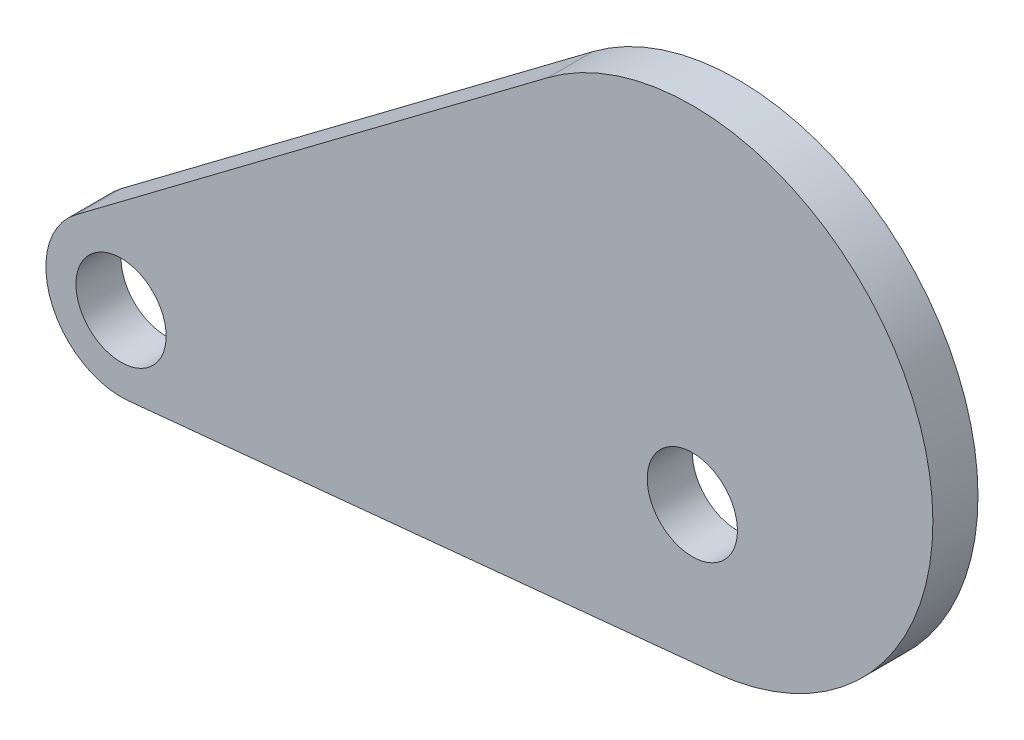
SolidWorks part; units mm, degrees
ref_plane "正面" through (0, 0, 0) normal (0, 0, 1) x (1, 0, 0)
ref_plane "平面" through (0, 0, 0) normal (0, 1, 0) x (1, 0, 0)
ref_plane "右側面" through (0, 0, 0) normal (1, 0, 0) x (0, 0, -1)
sketch "ｽｹｯﾁ1" plane through (0, 0, 0) normal (0, 0, 1) x (1, 0, 0)
  line L0 (9.387, 23.6902) -> (-22.0041, 0.0969)
  line L1 (19, -3.9) -> (-19, -3.9) construction
  line L2 (19, -3.9) -> (19, 3.9) construction
  line L3 (19, 3.9) -> (-19, 3.9) construction
  line L4 (-19, -3.9) -> (-19, 3.9) construction
  line L5 (19, -3.9) -> (-19, 3.9) construction
  line L6 (19, 3.9) -> (-19, -3.9) construction
  line L7 (-18.5094, -8.8759) -> (20.5699, -5.0228)
  circle A0 centre (-19, -3.9) radius 3
  circle A1 centre (19, 3.9) radius 3
  arc A2 (20.5699, -5.0228) -> (9.387, 23.6902) centre (19, 10.9) ccw
  arc A3 (-22.0041, 0.0969) -> (-18.5094, -8.8759) centre (-19, -3.9) ccw
  point P0 (0, 0)
  dimension "D3" = 6
  dimension "D5" = 16
  dimension "D6" = 5
  dimension "D7" = 5
  dimension "D8" = 5
  dimension "D1" = 38
  dimension "D2" = 7.8
  dimension "D4" = 7
extrude "ﾎﾞｽ - 押し出し1" add sketch "ｽｹｯﾁ1" along normal blind 3
